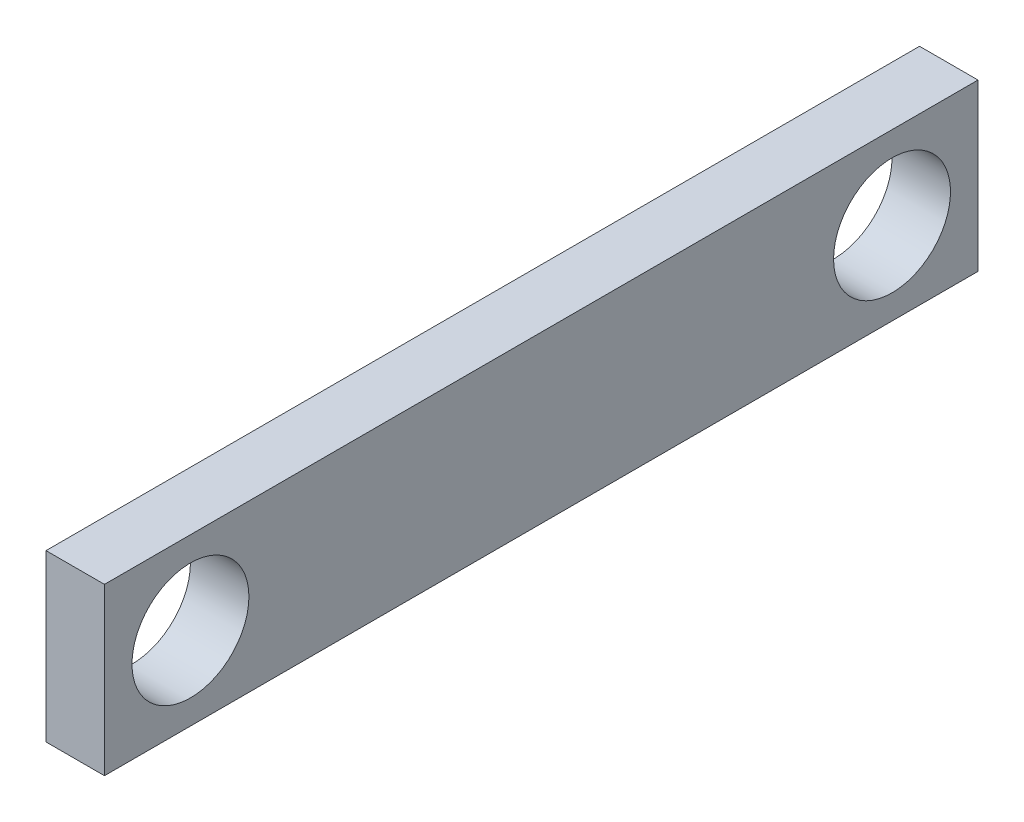
SolidWorks part; units mm, degrees
ref_plane "前基準面" through (0, 0, 0) normal (0, 0, 1) x (1, 0, 0)
ref_plane "上基準面" through (0, 0, 0) normal (0, 1, 0) x (1, 0, 0)
ref_plane "右基準面" through (0, 0, 0) normal (1, 0, 0) x (0, 0, -1)
sketch "Sketch1" plane through (0, 0, 0) normal (1, 0, 0) x (0, 0, -1)
  line L1 (-14.9414, -2.8348) -> (14.9414, -2.8348)
  line L2 (-14.9414, -2.8348) -> (-14.9414, 2.8348)
  line L3 (-14.9414, 2.8348) -> (14.9414, 2.8348)
  line L4 (14.9414, -2.8348) -> (14.9414, 2.8348)
  line L5 (0, 2.8348) -> (0, -2.8348) construction
  line L6 (-14.9414, 0) -> (14.9414, 0) construction
  circle A0 centre (-12, 0) radius 2
  circle A1 centre (12, 0) radius 2
  point P0 (0, 0)
  dimension "D1" = 24
  dimension "D2" = 4
extrude "Boss-Extrude1" add sketch "Sketch1" along normal blind 2
